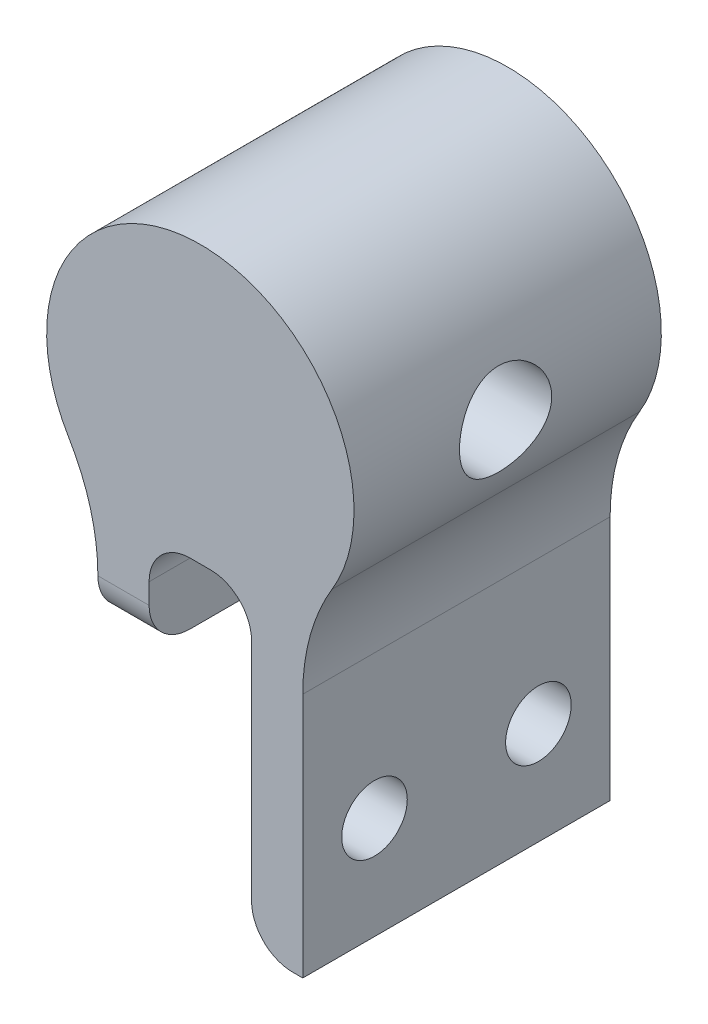
SolidWorks part; units mm, degrees
material "PUR"
ref_plane "Front Plane" through (0, 0, 0) normal (0, 0, 1) x (1, 0, 0)
ref_plane "Top Plane" through (0, 0, 0) normal (0, 1, 0) x (1, 0, 0)
ref_plane "Right Plane" through (0, 0, 0) normal (1, 0, 0) x (0, 0, -1)
sketch "Sketch2" plane through (0, 0, 0) normal (0, 0, 1) x (1, 0, 0)
  line L8 (0, 0) -> (0, -6.0083) construction
  line L9 (0, -6.0083) -> (0, -21.0083) construction
  line L10 (-2.5, -6.0083) -> (-2.5, -21.0083)
  line L11 (2.5, -6.0083) -> (2.5, -21.0083)
  line L12 (-5, -6.0083) -> (-5, -21.0083)
  line L13 (5, -6.0083) -> (5, -21.0083)
  line L14 (-5, -6.0083) -> (-5, -5.5902)
  line L15 (5, -6.0083) -> (5, -5.5902)
  line L16 (-5, -21.0083) -> (-2.5, -21.0083)
  line L17 (2.5, -21.0083) -> (5, -21.0083)
  line L18 (-2.5, -6.0083) -> (2.5, -6.0083)
  arc A0 (5, -5.5902) -> (-5, -5.5902) centre (0, 0) ccw
  dimension "D1" = 2.5
  dimension "D3" = 15
  dimension "D2" = 2.5
  dimension "D4" = 5
  dimension "D5" = 5
  dimension "D6" = 15
extrude "Boss-Extrude1" add sketch "Sketch2" along normal blind 15
fillet "Fillet2" radius 10 2 edges at (-5, -5.5902, 7.5) (5, -5.5902, 7.5)
sketch "Sketch8" plane through (5, 0, 0) normal (1, 0, 0) x (0, 0, -1)
  line L0 (-15, -21.0083) -> (0, -21.0083) construction
  line L1 (0, -21.0083) -> (0, -9.0139) construction
  circle A0 centre (-3.5, -16.0083) radius 1.6
  dimension "D1" = 3.2
  dimension "D2" = 5
  dimension "D3" = 3.5
extrude "Cut-Extrude6" cut sketch "Sketch8" against normal through all
sketch "Sketch9" plane through (-5, 0, 0) normal (-1, 0, 0) x (0, 0, 1)
  line L1 (15, -21.0083) -> (7.5, -21.0083)
  line L2 (15, -21.0083) -> (15, -11.0083)
  line L3 (15, -11.0083) -> (7.5, -11.0083)
  line L4 (7.5, -21.0083) -> (7.5, -11.0083)
  dimension "D1" = 10
  dimension "D2" = 7.5
extrude "Cut-Extrude7" cut sketch "Sketch9" against normal up to next
sketch "Sketch10" plane through (5, 0, 0) normal (1, 0, 0) x (0, 0, -1)
  line L0 (-15, -21.0083) -> (-15, -9.0139) construction
  line L1 (-15, -21.0083) -> (0, -21.0083) construction
  circle A0 centre (-11.5, -16.0083) radius 1.6
  dimension "D1" = 3.2
  dimension "D2" = 3.5
  dimension "D3" = 5
extrude "Cut-Extrude8" cut sketch "Sketch10" against normal up to next
fillet "Fillet3" radius 2 4 edges at (-2.5, -21.0083, 3.75) (2.5, -21.0083, 7.5) (2.5, -6.0083, 7.5) (-2.5, -6.0083, 7.5)
fillet "Fillet6" radius 2 2 edges at (-3.75, -11.0083, 15) (-3.75, -11.0083, 7.5)
sketch "Sketch11" plane through (0, 0, 0) normal (0, 0, -1) x (-1, 0, 0)
  circle A0 centre (0, 0) radius 2.05
  arc A1 (6.4286, -3.8631) -> (-6.4286, -3.8631) centre (0, 0) ccw construction
  dimension "D1" = 4.1
extrude "Cut-Extrude9" cut sketch "Sketch11" against normal blind 10
sketch "Sketch12" plane through (5, 0, 0) normal (1, 0, 0) x (0, 0, -1)
  line L1 (0, 7.5) -> (-15, 7.5) construction
  line L2 (0, -3.8631) -> (0, 7.5) construction
  circle A0 centre (-7.6, 0) radius 2.25
  dimension "D1" = 4.5
  dimension "D2" = 7.6
  dimension "D3" = 7.5
extrude "Cut-Extrude10" cut sketch "Sketch12" against normal mid plane 29
